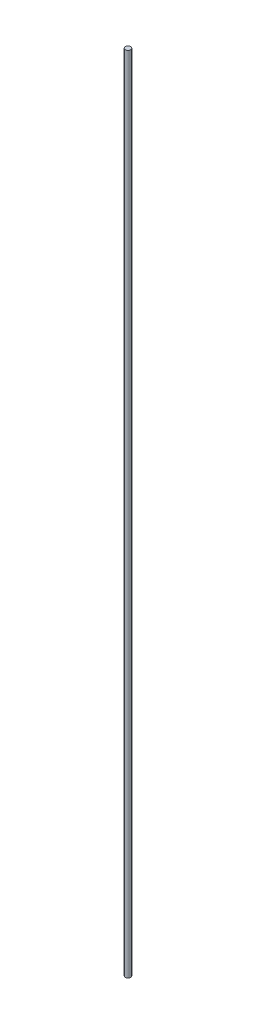
SolidWorks part; units mm, degrees
ref_plane "Front Plane" through (0, 0, 0) normal (0, 0, 1) x (1, 0, 0)
ref_plane "Top Plane" through (0, 0, 0) normal (0, 1, 0) x (1, 0, 0)
ref_plane "Right Plane" through (0, 0, 0) normal (1, 0, 0) x (0, 0, -1)
sketch "Sketch1" plane through (0, 0, 0) normal (0, 0, 1) x (1, 0, 0)
  line L0 (0, 0) -> (0, 1885.696)
  dimension "D1" = 1885.696
sweep "Sweep1" add path "Sketch1" circular profile diameter 12.7 parameters "D3"=12.7
